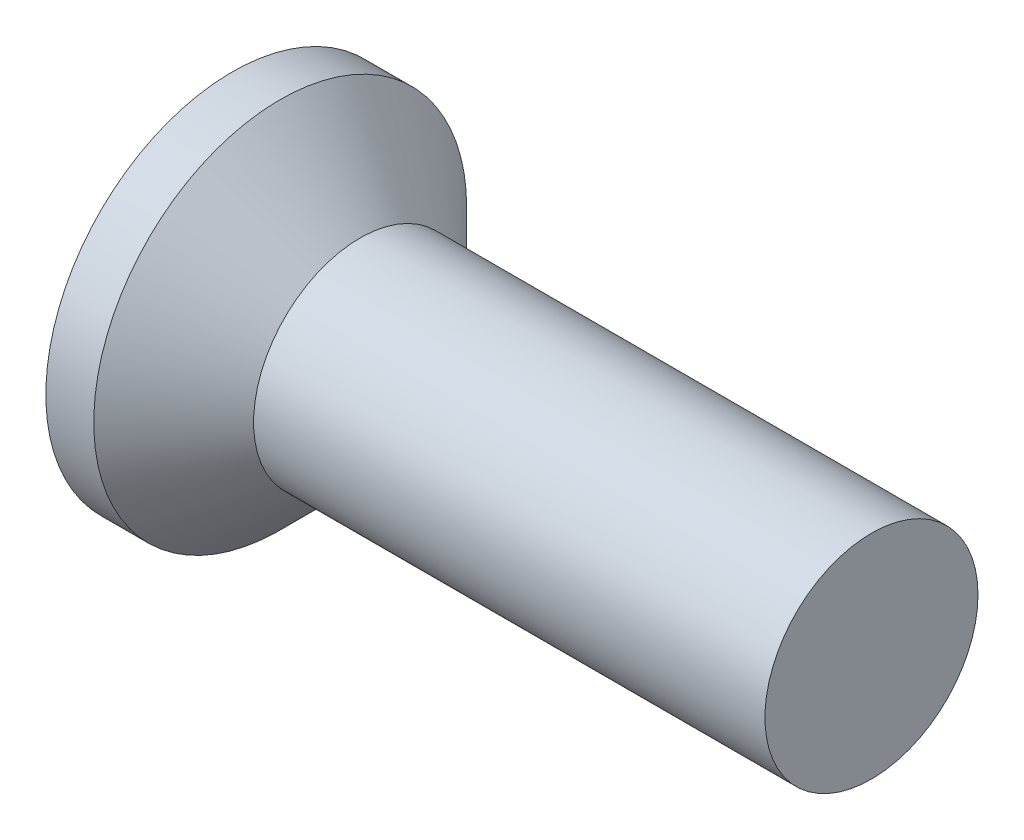
SolidWorks part; units mm, degrees
ref_plane "Front" through (0, 0, 0) normal (0, 0, 1) x (1, 0, 0)
ref_plane "Top" through (0, 0, 0) normal (0, 1, 0) x (1, 0, 0)
ref_plane "Right" through (0, 0, 0) normal (1, 0, 0) x (0, 0, -1)
sketch "Sketch1" plane through (0, 0, 0) normal (0, 0, 1) x (1, 0, 0)
  line L0 (6, 1) -> (2, 1)
  line L1 (2, 1) -> (1.2, 1)
  line L2 (1.2, 1) -> (0.45, 1.75)
  line L3 (0.45, 1.75) -> (0, 1.75)
  line L4 (6, 1) -> (6, 0)
  line L5 (4.5158, 0) -> (-89.8219, 0) construction
  line L6 (6, 0) -> (0, 0)
  line L7 (0, 1.75) -> (0, 0)
  dimension "D1" = 45
  dimension "d" = 2
  dimension "dk" = 3.5
  dimension "l" = 6
  dimension "k" = 1.2
  dimension "a" = 0.8
revolve "Base" add sketch "Sketch1" angle 360 about L5
cosmetic thread "ThreadCosmetic1" [suppressed] parameters "bb"=4.8, "THD_MINOR"=1.567
sketch "Sketch6" plane through (0, 0, 0) normal (1, 0, 0) x (0, 0, -1)
  line L0 (-1.9271, 0) -> (2.0512, 0) construction
  line L1 (0, 1.8651) -> (0, -2.0207) construction
  line L2 (0.19, 0.19) -> (0.19, 0.95)
  line L3 (0.19, 0.95) -> (-0.19, 0.95)
  line L4 (-0.19, 0.19) -> (-0.19, 0.95)
  line L5 (0.19, 0.19) -> (0.95, 0.19)
  line L6 (0.95, 0.19) -> (0.95, -0.19)
  line L7 (-0.95, 0.19) -> (-0.95, -0.19)
  line L8 (-0.19, 0.19) -> (-0.95, 0.19)
  line L9 (-0.19, -0.19) -> (-0.95, -0.19)
  line L10 (0.19, -0.19) -> (0.95, -0.19)
  line L11 (-0.19, -0.19) -> (-0.19, -0.95)
  line L12 (0.19, -0.95) -> (-0.19, -0.95)
  line L13 (0.19, -0.19) -> (0.19, -0.95)
  point P16 (-0.95, 0)
  point P17 (0.95, 0)
  dimension "D1" = 0.38
  dimension "m" = 1.9
extrude "CrossRecess" cut sketch "Sketch6" along normal blind 0.6
draft "Draft9" type of draft neutral plane draft angle 30 faces to draft 4 face at (0.3, 0.95, 0) face at (0.3, 0, 0.95) face at (0.3, -0.95, 0) face at (0.3, 0, -0.95) neutral plane through (0, 1.75, 0) neutral plane normal (-1, 0, 0) parameters "D1"=30
fillet "Fillet5" radius 0.3 4 edges at (0.3, -0.19, -0.19) (0.3, 0.19, -0.19) (0.3, 0.19, 0.19) (0.3, -0.19, 0.19)
sketch "Sketch7" plane through (0, 0, 0) normal (1, 0, 0) x (0, 0, -1)
  line L0 (-2.0126, 0) -> (1.9757, 0) construction
  line L1 (0, 1.9314) -> (0, -2.0126) construction
  line L2 (0, 0) -> (1.5555, 1.5555) construction
  line L3 (0, 0.2839) -> (0.6718, 0.6718)
  line L4 (-1.5402, 1.5402) -> (0, 0) construction
  line L5 (0.2839, 0) -> (0.6718, 0.6718)
  line L6 (0, -0.2839) -> (0.6718, -0.6718)
  line L7 (0.2839, 0) -> (0.6718, -0.6718)
  line L8 (-0.2839, 0) -> (-0.6718, -0.6718)
  line L9 (0, -0.2839) -> (-0.6718, -0.6718)
  line L10 (-0.2839, 0) -> (-0.6718, 0.6718)
  line L11 (0, 0.2839) -> (-0.6718, 0.6718)
  dimension "D3" = 15
extrude "Cut-Extrude3" [suppressed] cut sketch "Sketch7" along normal blind 10 draft 20
sketch "Sketch8" plane through (0, 0, 0) normal (0, 0, 1) x (1, 0, 0)
  line L0 (-19, 1.2165) -> (-20, 1)
  line L1 (-20, 1) -> (1.2, 1)
  line L3 (6, -1) -> (6, 1) construction
  line L6 (1.2, 1) -> (1.2, 6)
  line L7 (1.2, 6) -> (-19, 6)
  line L8 (-19, 6) -> (-19, 1.2165)
  line L9 (62.4753, 0.2165) -> (52.9594, 0.2165) construction
  dimension "D1" = 5
  dimension "x" = 1
  dimension "b" = 25
sketch "Sketch9" plane through (0, 0, 0) normal (0, 0, 1) x (1, 0, 0)
  line L0 (6, 0.8125) -> (6.1082, 1)
  line L1 (6.1082, 1) -> (6.1082, 1.2165)
  line L2 (6.1082, 1.2165) -> (5.8917, 1.2165)
  line L3 (5.8917, 1.2165) -> (5.8917, 1)
  line L4 (5.8917, 1) -> (6, 0.8125)
  line L5 (0, 0) -> (73.843, 0) construction
  line L6 (6, -1) -> (6, 1) construction
  dimension "D1" = 2
  dimension "D2" = 0.2165
revolve "Cut-Revolve10" [suppressed] cut sketch "Sketch9" angle 360 about L5
pattern_linear "LPattern10" [suppressed] count 18 spacing 0.2598 along (1, 0, 0)
equation "\"D1@Sketch6\" = \"m@Sketch6\" / 5"
equation "\"D1@CrossRecess\" = \"k@Sketch1\" / 2"
equation "\"D1@Sketch9\" = \"d@Sketch1\""
equation "\"D2@Sketch9\" =  ( \"d@Sketch1\" - \"THD_MINOR@ThreadCosmetic1\" )  / 2"
equation "\"D3@LPattern10\" = \"D2@Sketch9\" * 1.2"
equation "\"D1@LPattern10\" = \"bb@ThreadCosmetic1\" / \"D3@LPattern10\" "
